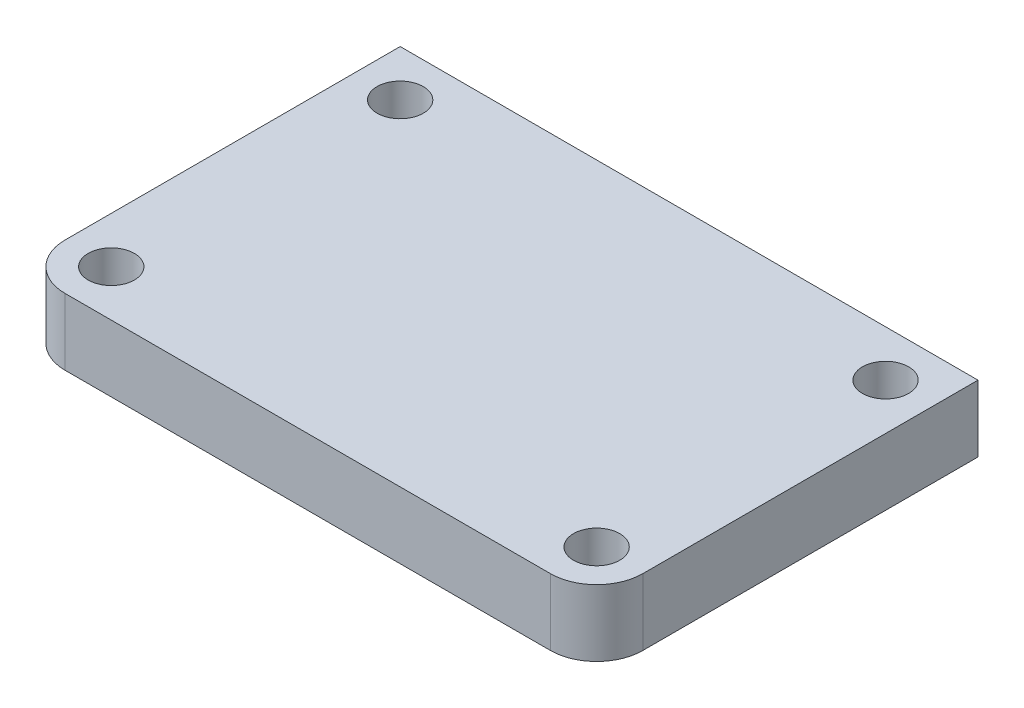
SolidWorks part; units mm, degrees
ref_plane "Front Plane" through (0, 0, 0) normal (0, 0, 1) x (1, 0, 0)
ref_plane "Top Plane" through (0, 0, 0) normal (0, 1, 0) x (1, 0, 0)
ref_plane "Right Plane" through (0, 0, 0) normal (1, 0, 0) x (0, 0, -1)
sketch "Sketch1" plane through (0, 0, 0) normal (0, 1, 0) x (1, 0, 0)
  line L1 (-12.5, -12) -> (12.5, -12)
  line L2 (-12.5, -12) -> (-12.5, 12)
  line L3 (-12.5, 12) -> (12.5, 12)
  line L4 (12.5, -12) -> (12.5, 12)
  line L5 (-12.5, -12) -> (12.5, 12) construction
  line L6 (-12.5, 12) -> (12.5, -12) construction
  line L7 (-12.5, 12) -> (12.5, 12)
  line L8 (-12.5, 12) -> (-12.5, 4.5)
  line L9 (-12.5, 4.5) -> (12.5, 4.5)
  line L10 (12.5, 12) -> (12.5, 4.5)
  point P0 (0, 0)
  dimension "D1" = 25
  dimension "D2" = 24
  dimension "D3" = 7.5
extrude "Boss-Extrude1" add sketch "Sketch1" along normal blind 2.88 contours L9 L2 L1 L4
sketch "Sketch2" plane through (0, 2.88, 0) normal (0, 1, 0) x (1, 0, 0)
  line L0 (-12.5, -12) -> (12.5, -12) construction
  line L1 (-12.5, -12) -> (-12.5, 4.5) construction
  circle A0 centre (-10.5, 2.5) radius 1
  circle A1 centre (-10.5, -10) radius 1
  circle A2 centre (10.5, -10) radius 1
  circle A3 centre (10.5, 2.5) radius 1
  dimension "D1" = 2
  dimension "D2" = 2
  dimension "D3" = 2
  dimension "D4" = 2
  dimension "D5" = 12.5
  dimension "D7" = 21
  dimension "D8" = 21
  dimension "D9" = 2
  dimension "D10" = 2
  dimension "D11" = 2
  dimension "D12" = 2
  dimension "D6" = 12.5
extrude "Cut-Extrude1" cut sketch "Sketch2" against normal through all
fillet "Fillet1" radius 2 2 edges at (12.5, 1.44, 12) (-12.5, 1.44, 12)
